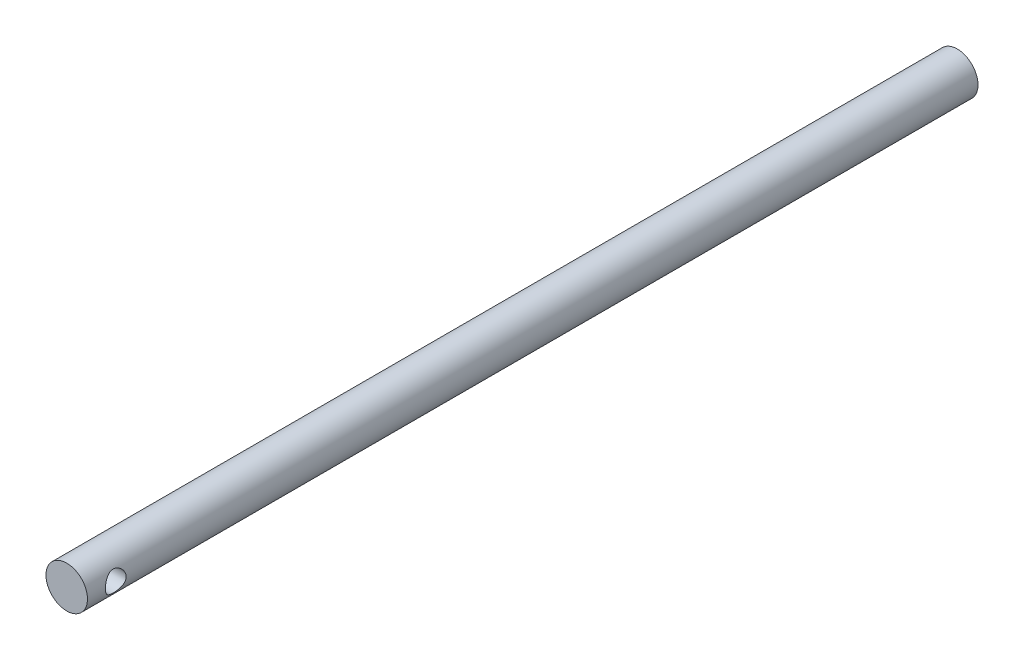
SolidWorks part; units mm, degrees
ref_plane "Front Plane" through (0, 0, 0) normal (0, 0, 1) x (1, 0, 0)
ref_plane "Top Plane" through (0, 0, 0) normal (0, 1, 0) x (1, 0, 0)
ref_plane "Right Plane" through (0, 0, 0) normal (1, 0, 0) x (0, 0, -1)
sketch "Sketch1" plane through (0, 0, 0) normal (0, 0, 1) x (1, 0, 0)
  circle A0 centre (0, 0) radius 4.763
  dimension "D1" = 9.526
extrude "Boss-Extrude1" add sketch "Sketch1" along normal blind 204.364
sketch "Sketch2" plane through (0, 0, 0) normal (1, 0, 0) x (0, 0, -1)
  line L0 (-204.364, 4.763) -> (-204.364, -4.763) construction
  line L1 (0, 4.763) -> (-204.364, 4.763) construction
  circle A0 centre (-197.864, 0) radius 2.3815
  dimension "D1" = 4.763
  dimension "D3" = 4.763
  dimension "D2" = 6.5
extrude "Cut-Extrude1" cut sketch "Sketch2" against normal through all both and the other way through all
